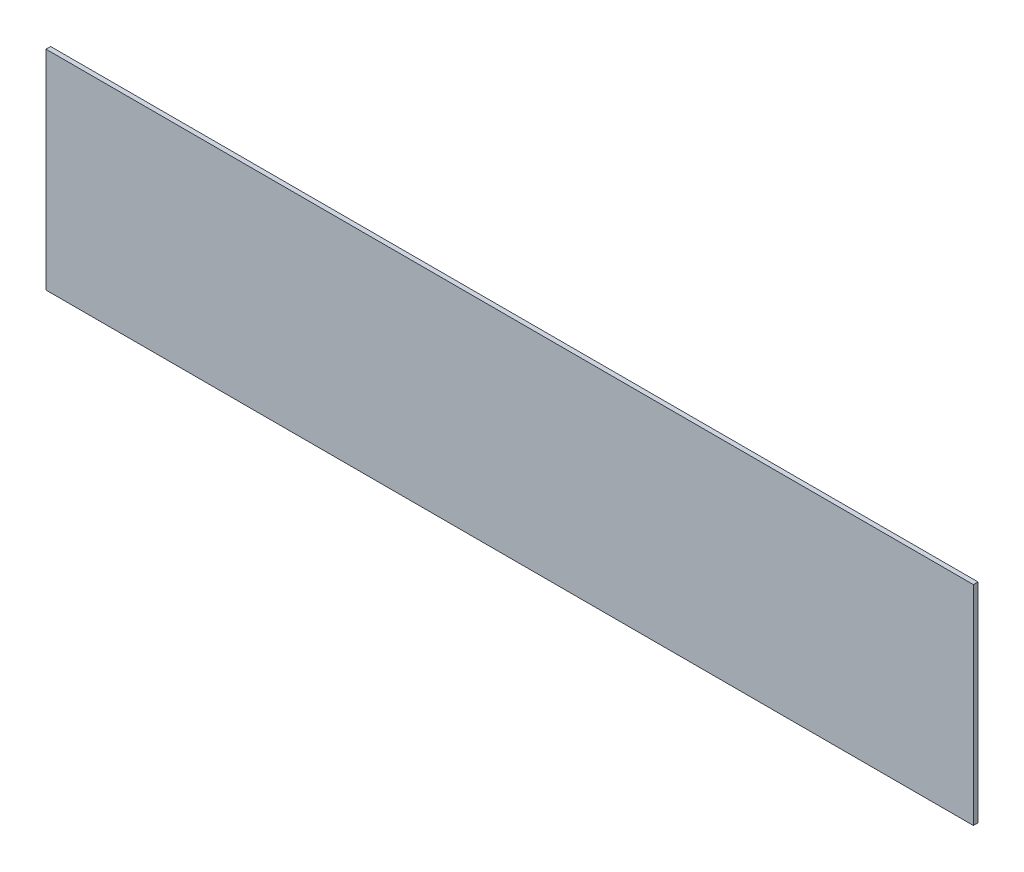
SolidWorks part; units mm, degrees
ref_plane "Ebene vorne" through (0, 0, 0) normal (0, 0, 1) x (1, 0, 0)
ref_plane "Ebene oben" through (0, 0, 0) normal (0, 1, 0) x (1, 0, 0)
ref_plane "Ebene rechts" through (0, 0, 0) normal (1, 0, 0) x (0, 0, -1)
sketch "Sketch2" plane through (0, 0, 0) normal (1, 0, 0) x (0, 0, -1)
  line L1 (0, 0) -> (2, 0)
  line L2 (0, 0) -> (0, 90)
  line L3 (0, 90) -> (2, 90)
  line L4 (2, 0) -> (2, 90)
  dimension "D1" = 2
  dimension "D2" = 90
extrude "Boss-Extrude1" add sketch "Sketch2" along normal blind 400
